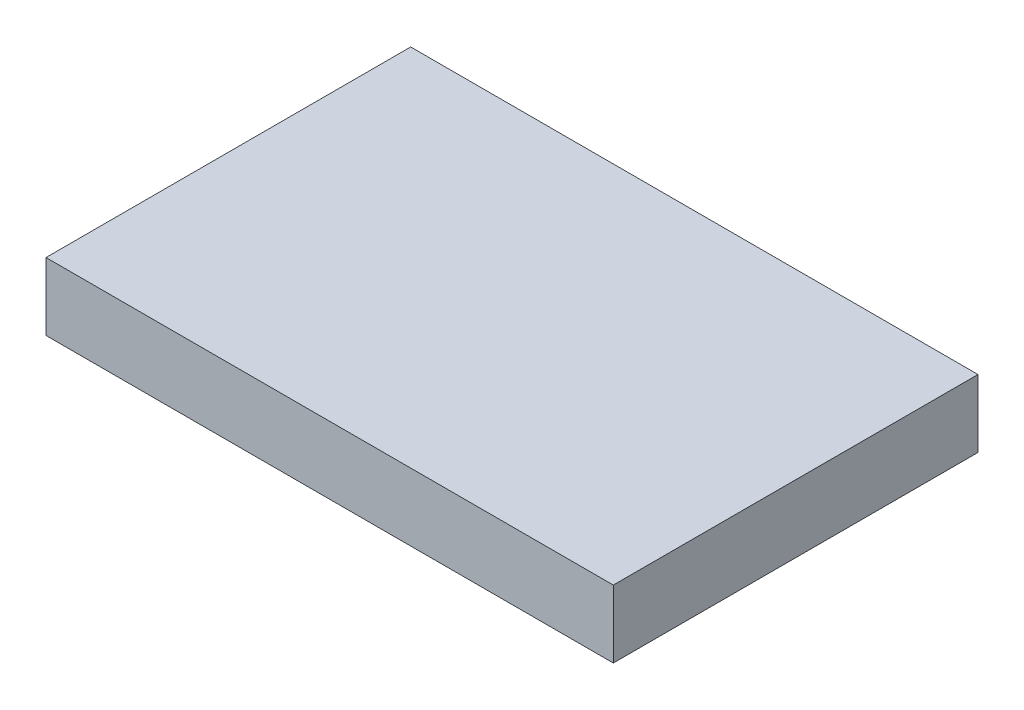
SolidWorks part; units mm, degrees
ref_plane "Front Plane" through (0, 0, 0) normal (0, 0, 1) x (1, 0, 0)
ref_plane "Top Plane" through (0, 0, 0) normal (0, 1, 0) x (1, 0, 0)
ref_plane "Right Plane" through (0, 0, 0) normal (1, 0, 0) x (0, 0, -1)
sketch "Sketch1" plane through (0, 0, 0) normal (0, 1, 0) x (1, 0, 0)
  line L1 (-42, -27) -> (42, -27)
  line L2 (-42, -27) -> (-42, 27)
  line L3 (-42, 27) -> (42, 27)
  line L4 (42, -27) -> (42, 27)
  line L5 (-42, -27) -> (42, 27) construction
  line L6 (-42, 27) -> (42, -27) construction
  point P0 (0, 0)
  dimension "D1" = 84
  dimension "D2" = 54
extrude "Boss-Extrude1" add sketch "Sketch1" along normal blind 10
